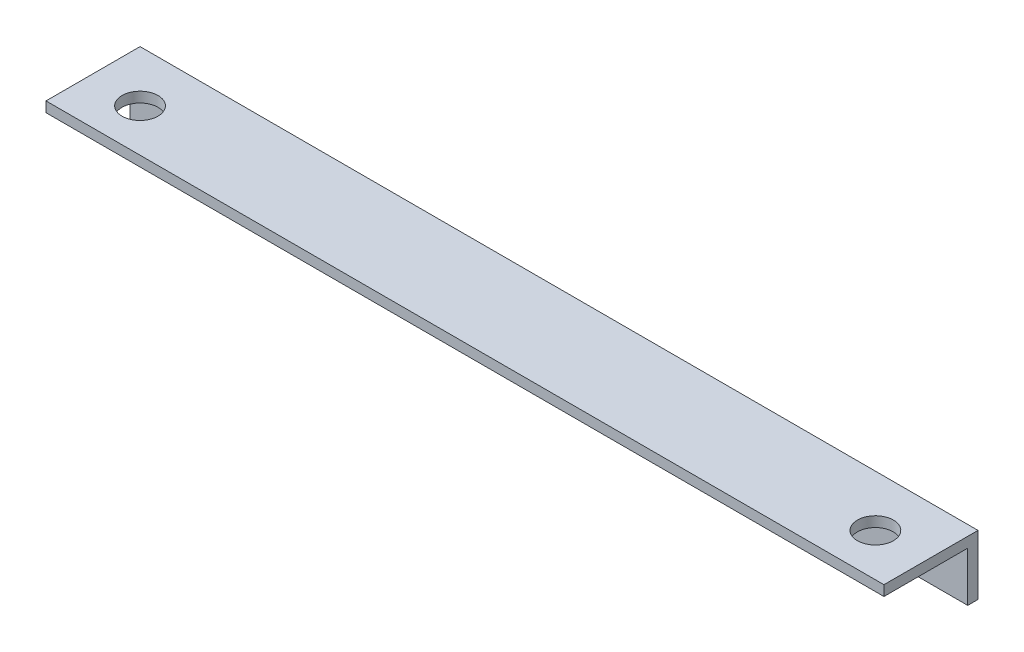
SolidWorks part; units mm, degrees
ref_plane "Front Plane" through (0, 0, 0) normal (0, 0, 1) x (1, 0, 0)
ref_plane "Top Plane" through (0, 0, 0) normal (0, 1, 0) x (1, 0, 0)
ref_plane "Right Plane" through (0, 0, 0) normal (1, 0, 0) x (0, 0, -1)
sketch "Sketch1" plane through (0, 0, 0) normal (0, 0, 1) x (1, 0, 0)
  line L0 (0, -55) -> (0, 55) construction
  line L1 (-49, -3.5) -> (49, -3.5)
  line L2 (-49, -3.5) -> (-49, 3.5)
  line L3 (-49, 3.5) -> (49, 3.5)
  line L4 (49, -3.5) -> (49, 3.5)
  line L5 (-49, -3.5) -> (49, 3.5) construction
  line L6 (-49, 3.5) -> (49, -3.5) construction
  circle A0 centre (-35, -0.7) radius 1.6
  circle A1 centre (35, -0.7) radius 1.6
  point P0 (0, 0)
  dimension "D4" = 3.2
  dimension "D1" = 98
  dimension "D2" = 4.2
  dimension "D3" = 35
  dimension "D5" = 7
extrude "Boss-Extrude1" add sketch "Sketch1" along normal blind 1.2
sketch "Sketch2" plane through (0, 3.5, 0) normal (0, 1, 0) x (1, 0, 0)
  line L0 (49, 0) -> (-49, 0) construction
  line L1 (-49, -1.2) -> (49, -1.2)
  line L2 (-49, -1.2) -> (-49, -11)
  line L3 (-49, -11) -> (49, -11)
  line L4 (49, -1.2) -> (49, -11)
  line L5 (0, -0.66) -> (0, 0.66) construction
  circle A0 centre (-43, -6) radius 2.1
  circle A1 centre (43, -6) radius 2.1
  point P10 (0, 0)
  dimension "D3" = 43
  dimension "D5" = 4.2
  dimension "D1" = 0
  dimension "D2" = 11
  dimension "D4" = 6
extrude "Boss-Extrude2" add sketch "Sketch2" against normal blind 1.2
